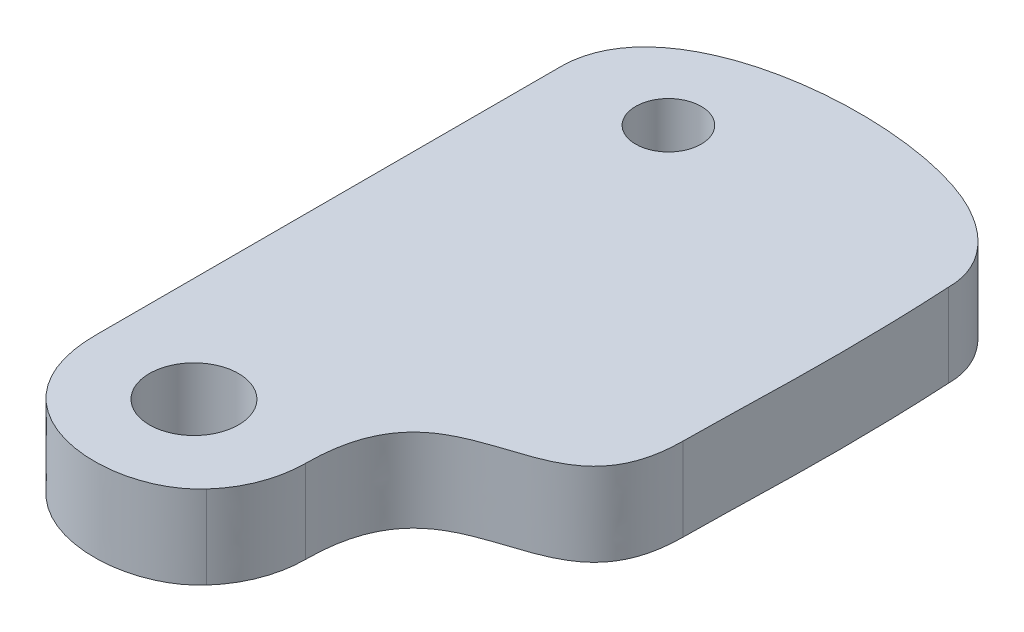
SolidWorks part; units mm, degrees
material "Acrylic (Medium-high impact)"
ref_plane "Front Plane" through (0, 0, 0) normal (0, 0, 1) x (1, 0, 0)
ref_plane "Top Plane" through (0, 0, 0) normal (0, 1, 0) x (1, 0, 0)
ref_plane "Right Plane" through (0, 0, 0) normal (1, 0, 0) x (0, 0, -1)
sketch "Sketch1" plane through (0, 0, 0) normal (0, 1, 0) x (1, 0, 0)
  line L0 (-4.7359, 8.1473) -> (-2.0906, 8.1473) construction
  line L1 (-7.4061, 8.0473) -> (-7.4061, -9.6675)
  line L2 (-4.9105, -9.9531) -> (-1.9158, -9.9533) construction
  circle A0 centre (-3.4132, -9.9532) radius 1.7
  circle A1 centre (-3.4133, 8.1473) radius 1.25
  spline S0 degree 3 poles (-7.4061, -9.6675) (-7.4274, -14.3593) (-2.105, -14.8224) (-0.2112, -12.6848) knots 3 3 3 3 4 4 4 4
  spline S1 degree 3 poles (-0.2112, -12.6848) (0.4548, -11.9615) (0.8309, -10.9791) (0.8342, -9.9533) knots 4 4 4 4 5 5 5 5
  spline S2 degree 3 poles (0.8342, -9.9533) (0.8476, -3.7592) (7.2767, -7.4622) (7.2998, -2.009) knots 5 5 5 5 6 6 6 6
  spline S3 degree 3 poles (7.2998, -2.009) (7.31, 0.4563) (7.5237, 3.7521) (7.2767, 8.1473) knots 6 6 6 6 7 7 7 7
  spline S4 degree 3 poles (7.2767, 8.1473) (7.2872, 9.1731) (6.6323, 10.1637) (5.4568, 10.9009) knots 7 7 7 7 8 8 8 8
  spline S5 degree 3 poles (5.4568, 10.9009) (2.107, 13.0814) (-7.3869, 12.7393) (-7.4061, 8.0473) knots 8 8 8 8 9 9 9 9
  dimension "D1" = 3.4
  dimension "D2" = 2.5
extrude "Boss-Extrude1" add sketch "Sketch1" along normal blind 3.175
